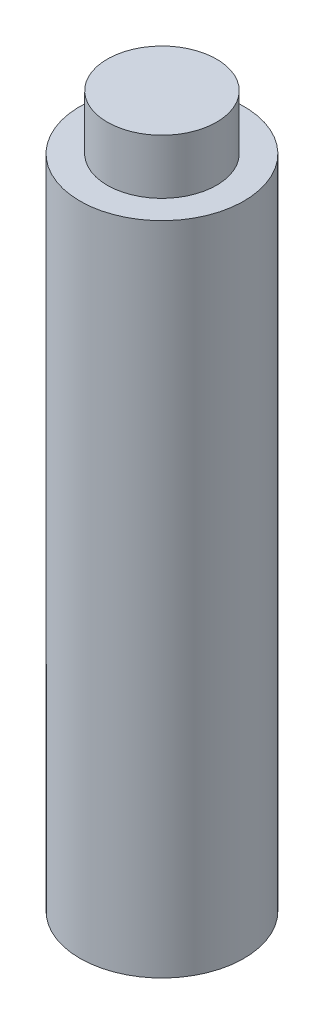
SolidWorks part; units mm, degrees
ref_plane "正面" through (0, 0, 0) normal (0, 0, 1) x (1, 0, 0)
ref_plane "平面" through (0, 0, 0) normal (0, 1, 0) x (1, 0, 0)
ref_plane "右側面" through (0, 0, 0) normal (1, 0, 0) x (0, 0, -1)
sketch "ｽｹｯﾁ1" plane through (0, 0, 0) normal (0, 1, 0) x (1, 0, 0)
  circle A0 centre (0, 0) radius 7.5
  dimension "D1" = 15
extrude "ﾎﾞｽ - 押し出し1" add sketch "ｽｹｯﾁ1" along normal blind 60
sketch "ｽｹｯﾁ2" plane through (0, 60, 0) normal (0, 1, 0) x (1, 0, 0)
  circle A0 centre (0, 0) radius 5
  dimension "D1" = 10
extrude "ﾎﾞｽ - 押し出し2" add sketch "ｽｹｯﾁ2" along normal blind 5
sketch "ｽｹｯﾁ3" plane through (0, 0, 0) normal (0, -1, 0) x (1, 0, 0)
  circle A0 centre (0, 0) radius 5.1
  dimension "D1" = 10.2
extrude "ｶｯﾄ - 押し出し1" cut sketch "ｽｹｯﾁ3" against normal blind 5
